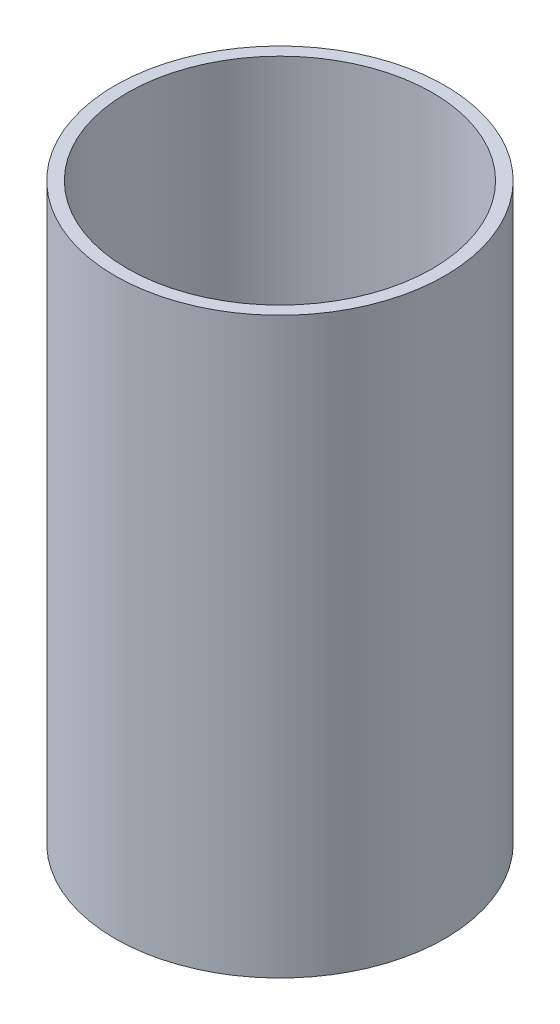
SolidWorks part; units mm, degrees
ref_plane "Front Plane" through (0, 0, 0) normal (0, 0, 1) x (1, 0, 0)
ref_plane "Top Plane" through (0, 0, 0) normal (0, 1, 0) x (1, 0, 0)
ref_plane "Right Plane" through (0, 0, 0) normal (1, 0, 0) x (0, 0, -1)
sketch "Sketch1" plane through (0, 0, 0) normal (0, 1, 0) x (1, 0, 0)
  circle A0 centre (0, 0) radius 33.1
  dimension "D1" = 66.2
extrude "Boss-Extrude1" add sketch "Sketch1" along normal blind 115.2 contours A0
shell "Shell1" thickness 2.5
sketch "Sketch2" plane through (0, 115.2, 0) normal (0, 1, 0) x (1, 0, 0)
  circle A0 centre (0, 0) radius 30.6 construction
  circle A1 centre (0, 0) radius 30.6
extrude "Cut-Extrude1" cut sketch "Sketch2" against normal blind 30
